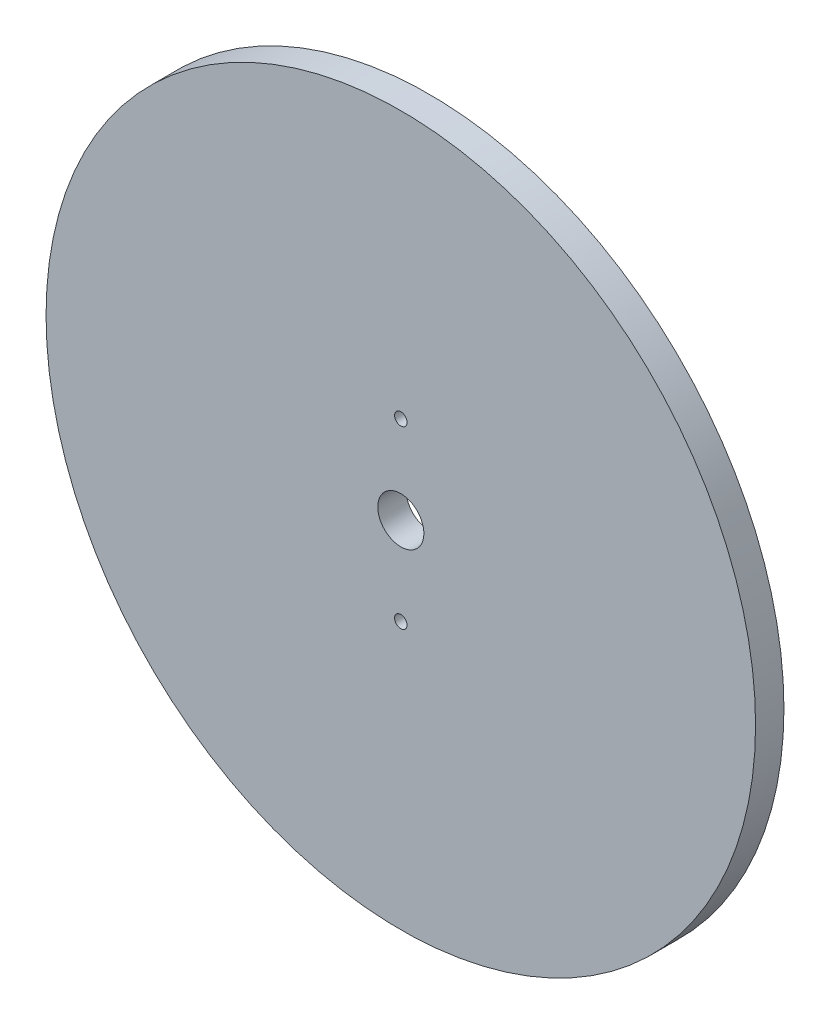
SolidWorks part; units mm, degrees
ref_plane "Front Plane" through (0, 0, 0) normal (0, 0, 1) x (1, 0, 0)
ref_plane "Top Plane" through (0, 0, 0) normal (0, 1, 0) x (1, 0, 0)
ref_plane "Right Plane" through (0, 0, 0) normal (1, 0, 0) x (0, 0, -1)
sketch "Sketch1" plane through (0, 0, 0) normal (0, 0, 1) x (1, 0, 0)
  circle A0 centre (0, 0) radius 100
extrude "Boss-Extrude1" add sketch "Sketch1" along normal blind 8
sketch "Sketch2" plane through (0, 0, 0) normal (0, 0, 1) x (1, 0, 0)
  circle A0 centre (0, 24.75) radius 1.75
  circle A1 centre (0, -24.75) radius 1.75
  circle A2 centre (0, 0) radius 6.5
extrude "Cut-Extrude2" cut sketch "Sketch2" along normal blind 9
